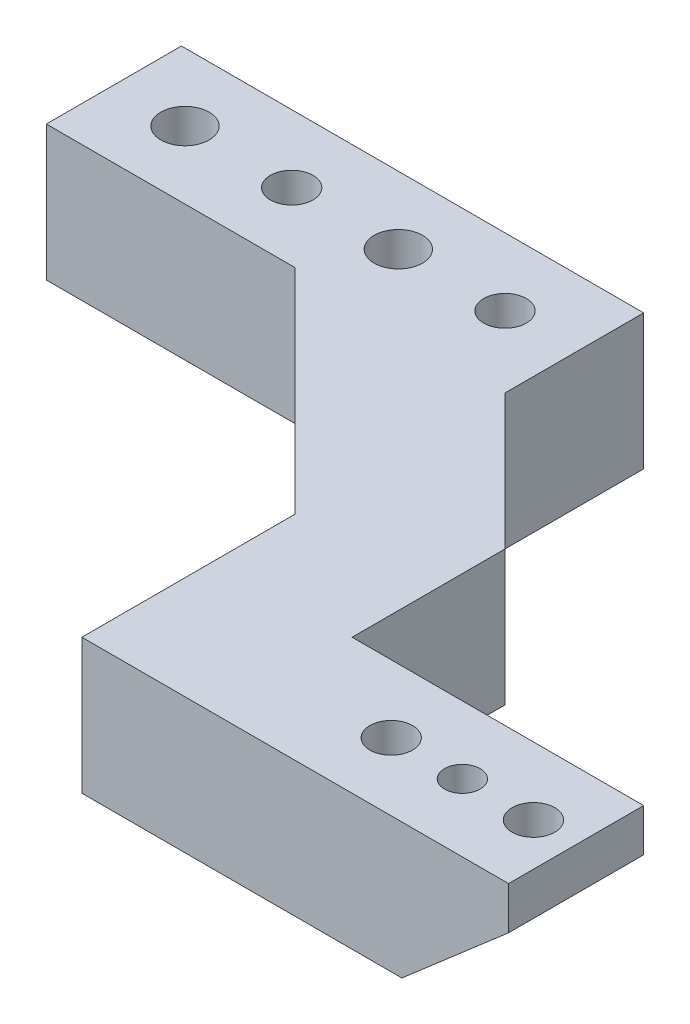
SolidWorks part; units mm, degrees
material "Q235A"
ref_plane "前视" through (0, 0, 0) normal (0, 0, 1) x (1, 0, 0)
ref_plane "上视" through (0, 0, 0) normal (0, 1, 0) x (1, 0, 0)
ref_plane "右视" through (0, 0, 0) normal (1, 0, 0) x (0, 0, -1)
sketch "草图1" plane through (0, 0, 0) normal (0, 1, 0) x (1, 0, 0)
  line L1 (32.5, -9.5) -> (-32.5, -9.5)
  line L2 (32.5, -9.5) -> (32.5, 9.5)
  line L3 (32.5, 9.5) -> (-32.5, 9.5)
  line L4 (-32.5, -9.5) -> (-32.5, 9.5)
  line L5 (32.5, -9.5) -> (-32.5, 9.5) construction
  line L6 (32.5, 9.5) -> (-32.5, -9.5) construction
  point P0 (0, 0)
  dimension "D1" = 19
  dimension "D2" = 65
extrude "凸台-拉伸1" add sketch "草图1" along normal blind 19
hole_wizard "M8 螺纹孔2" positions "草图3" profile "草图2" tap size "M8" standard "GB" end condition through all
sketch "草图3" plane through (0, 19, 0) normal (0, 1, 0) x (1, 0, 0)
  line L0 (-32.5, 9.5) -> (-32.5, -9.5) construction
  point P0 (-22.5, 0)
  point P2 (7.5, 0)
  dimension "D1" = 30
  dimension "D2" = 10
sketch "草图2" plane through (-22.5, 19, 0) normal (1, 0, 0) x (0, 0, 1)
  line L0 (0, 0) -> (0, 19)
  line L1 (0, 19) -> (3.4, 19)
  line L2 (3.4, 19) -> (3.4, 0)
  line L5 (3.4, 0) -> (0, 0)
  line L11 (0, -6.35) -> (0, 107.95) construction
  dimension "通孔螺纹孔钻头直径" = 6.8
  dimension "通孔螺纹孔钻头深度" = 19
cosmetic thread "孔螺蚊线3" parameters "D2"=8
cosmetic thread "孔螺蚊线4" parameters "D2"=8
hole_wizard "大小mm 暗销孔2" positions "草图5" profile "草图4" hole size "Ø6.0" standard "GB"
sketch "草图5" plane through (0, 0, 0) normal (0, 1, 0) x (1, 0, 0)
  circle A0 centre (-22.5, 0) radius 3.4 construction
  point P0 (-7.5, 0)
  point P2 (22.5, 0)
  dimension "D1" = 15
  dimension "D2" = 30
sketch "草图4" plane through (-7.5, 0, 0) normal (1, 0, 0) x (0, 0, -1)
  line L0 (0, 0) -> (0, 21.8026)
  line L1 (0, 21.8026) -> (3, 20)
  line L2 (3, 20) -> (3, 0)
  line L5 (3, 0) -> (0, 0)
  line L10 (0, 21.8026) -> (-3, 20) construction
  line L11 (0, -6.35) -> (0, 107.95) construction
  dimension "孔直径" = 6
  dimension "孔深度" = 20
  dimension "导头角度" = 118
sketch "草图6" plane through (32.5, 0, 0) normal (1, 0, 0) x (0, 0, -1)
  line L0 (50, 0) -> (-50, 0) construction
  line L1 (-69.5, 19) -> (9.5, 19)
  line L2 (-69.5, 19) -> (-69.5, 0)
  line L3 (-69.5, 0) -> (9.5, 0)
  line L4 (9.5, 19) -> (9.5, 0)
  line L5 (9.5, 19) -> (9.5, 0) construction
  line L6 (-9.5, 19) -> (-9.5, 0) construction
  dimension "D1" = 60
extrude "凸台-拉伸2" add sketch "草图6" along normal blind 60
hole_wizard "大小mm 暗销孔3" positions "草图8" profile "草图7" hole size "Ø6.0" standard "GB" end condition through all
sketch "草图8" plane through (0, 19, 0) normal (0, 1, 0) x (1, 0, 0)
  line L1 (92.5, 9.5) -> (92.5, -69.5) construction
  line L3 (92.5, -69.5) -> (32.5, -69.5) construction
  point P0 (86.5, -60)
  point P2 (66.5, -60)
  dimension "D1" = 20
  dimension "D2" = 6
  dimension "D3" = 9.5
sketch "草图7" plane through (86.5, 19, 60) normal (1, 0, 0) x (0, 0, 1)
  line L0 (0, 0) -> (0, 19.0001)
  line L1 (0, 19.0001) -> (3, 19.0001)
  line L2 (3, 19.0001) -> (3, 0)
  line L5 (3, 0) -> (0, 0)
  line L11 (0, -6.35) -> (0, 107.95) construction
  dimension "通孔孔直径" = 6
  dimension "通孔孔深度" = 19.0001
hole_wizard "M6 螺纹孔1" positions "草图10" profile "草图9" tap size "M6" standard "GB" end condition through all
sketch "草图10" plane through (0, 19, 0) normal (0, 1, 0) x (1, 0, 0)
  line L0 (66.5, -60) -> (76.5, -60) construction
  circle A0 centre (66.5, -60) radius 3 construction
  point P0 (76.5, -60)
  dimension "D1" = 10
sketch "草图9" plane through (76.5, 19, 60) normal (1, 0, 0) x (0, 0, 1)
  line L0 (0, 0) -> (0, 19.0001)
  line L1 (0, 19.0001) -> (2.5, 19.0001)
  line L2 (2.5, 19.0001) -> (2.5, 0)
  line L5 (2.5, 0) -> (0, 0)
  line L11 (0, -6.35) -> (0, 107.95) construction
  dimension "通孔螺纹孔钻头直径" = 5
  dimension "通孔螺纹孔钻头深度" = 19.0001
cosmetic thread "孔螺蚊线5" parameters "D2"=6
chamfer "倒角2" distance 30 angle 45 1 edges
sketch "草图11" plane through (0, 0, 0) normal (0, -1, 0) x (-1, 0, 0)
  line L0 (-51.5, -50.5) -> (-95.0748, -50.5)
  line L1 (-95.0748, -50.5) -> (-95.0748, 28.6917)
  line L2 (-95.0748, 28.6917) -> (-32.5, 28.6917)
  line L3 (-32.5, 28.6917) -> (-32.5, -10.0243)
  line L4 (-32.5, -10.0243) -> (-51.5, -29.0243)
  line L5 (-51.5, -29.0243) -> (-51.5, -50.5)
  line L6 (-32.5, -39.5) -> (-2.5, -9.5) construction
  line L7 (-92.5, -69.5) -> (-32.5, -69.5) construction
  line L8 (-32.5, -69.5) -> (-32.5, -39.5) construction
  line L9 (32.5, 9.5) -> (32.5, -9.5) construction
  dimension "D1" = 19
  dimension "D2" = 19
  dimension "D3" = 65
extrude "切除-拉伸1" cut sketch "草图11" against normal through all
sketch "草图12" plane through (0, 0, 69.5) normal (0, 0, 1) x (1, 0, 0)
  line L0 (92.5, 13) -> (77.5, 0)
  line L1 (92.5, 19) -> (92.5, 0) construction
  line L2 (92.5, 0) -> (32.5, 0) construction
  line L3 (92.5, 19) -> (32.5, 19) construction
  dimension "D1" = 6
  dimension "D2" = 15
extrude "切除-拉伸2" cut sketch "草图12" against normal through all and the other way through all
